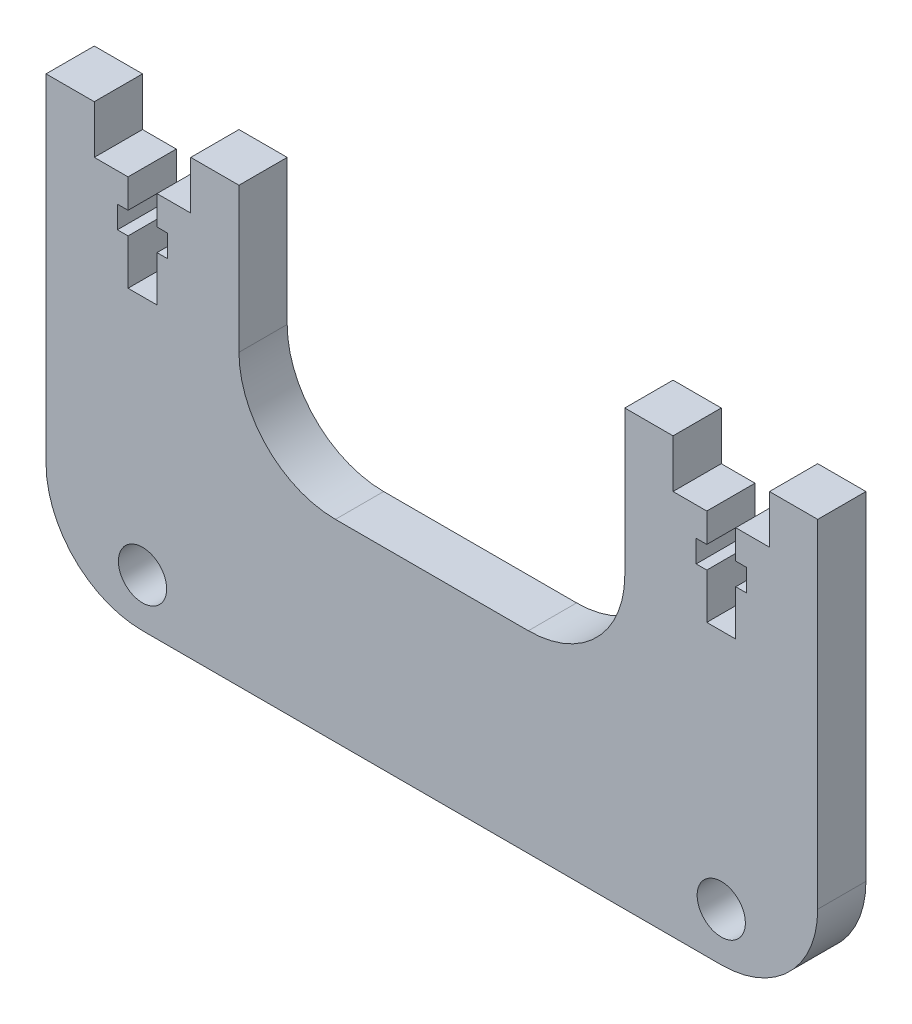
SolidWorks part; units mm, degrees
ref_plane "Plan de face" through (0, 0, 0) normal (0, 0, 1) x (1, 0, 0)
ref_plane "Plan de dessus" through (0, 0, 0) normal (0, 1, 0) x (1, 0, 0)
ref_plane "Plan de droite" through (0, 0, 0) normal (1, 0, 0) x (0, 0, -1)
sketch "Esquisse1" plane through (0, 0, 0) normal (0, 0, 1) x (1, 0, 0)
  line L0 (0, 0) -> (40, 0) construction
  line L1 (0, 0) -> (0, 31.2901) construction
  line L2 (-40, 0) -> (-40, -40)
  line L3 (-40, -40) -> (40, -40)
  line L4 (40, -40) -> (40, 0)
  line L5 (-20, 0) -> (-20, -20)
  line L6 (-20, -20) -> (20, -20)
  line L7 (20, -20) -> (20, 0)
  line L8 (-40, -35) -> (40, -35) construction
  circle A0 centre (-30, -35) radius 2.5
  circle A2 centre (30, -35) radius 2.5
  line B0 (32.6, -3) -> (32.6, -5.3)
  line B1 (28.5, -5.3) -> (28.5, -10)
  line B2 (31.5, -10) -> (31.5, -5.3)
  line B3 (32.6, -5.3) -> (31.5, -5.3)
  line B4 (30, 0) -> (30, -11.2208) construction
  line B5 (31.5, 0) -> (35, 0)
  line B6 (35, 5) -> (40, 5)
  line B7 (40, 5) -> (40, 0)
  line B8 (35, 5) -> (35, 0)
  line B9 (28.5, 0) -> (25, 0)
  line B10 (25, 0) -> (25, 5)
  line B11 (25, 5) -> (20, 5)
  line B12 (20, 5) -> (20, 0)
  line B13 (31.5, 0) -> (28.5, 0) construction
  line B14 (28.5, 0) -> (28.5, -3)
  line B15 (28.5, -5.3) -> (27.4, -5.3)
  line B16 (27.4, -3) -> (28.5, -3)
  line B17 (28.5, -10) -> (31.5, -10)
  line B18 (31.5, -3) -> (32.6, -3)
  line B19 (27.4, -5.3) -> (27.4, -3)
  line B20 (31.5, -3) -> (31.5, 0)
  line B21 (30, -10) -> (30, 0) construction
  line B22 (-32.6, -3) -> (-32.6, -5.3)
  line B23 (-28.5, -5.3) -> (-28.5, -10)
  line B24 (-31.5, -10) -> (-31.5, -5.3)
  line B25 (-32.6, -5.3) -> (-31.5, -5.3)
  line B26 (-30, 0) -> (-30, -11.2208) construction
  line B27 (-31.5, 0) -> (-35, 0)
  line B28 (-35, 5) -> (-40, 5)
  line B29 (-40, 5) -> (-40, 0)
  line B30 (-35, 5) -> (-35, 0)
  line B31 (-28.5, 0) -> (-25, 0)
  line B32 (-25, 0) -> (-25, 5)
  line B33 (-25, 5) -> (-20, 5)
  line B34 (-20, 5) -> (-20, 0)
  line B35 (-31.5, 0) -> (-28.5, 0) construction
  line B36 (-28.5, 0) -> (-28.5, -3)
  line B37 (-28.5, -5.3) -> (-27.4, -5.3)
  line B38 (-27.4, -3) -> (-28.5, -3)
  line B39 (-28.5, -10) -> (-31.5, -10)
  line B40 (-31.5, -3) -> (-32.6, -3)
  line B41 (-27.4, -5.3) -> (-27.4, -3)
  line B42 (-31.5, -3) -> (-31.5, 0)
  line B43 (-30, -10) -> (-30, 0) construction
  dimension "D5" = 5
  dimension "D1" = 60
  dimension "D2" = 20
  dimension "D3" = 20
  dimension "D4" = 5
sketch_block_instance "Insert M3 plots ep 5mm-1"
sketch_block "Insert M3 plots ep 5mm" parameters "D1"=10, "D2"=5, "D3"=5
sketch_block_instance "Decoupe Insert M3-4"
sketch_block "Decoupe Insert M3" parameters "D1"=5.2, "D2"=3, "D3"=2.3, "D4"=3, "D5"=10
sketch_block_instance "Insert M3 plots ep 5mm-3"
extrude "Boss.-Extru.1" add sketch "Esquisse1" along normal blind 5 contours B40 B42 B27 B30 B28 B29 L2 L3 L4 B7 B6 B8 B5 B20 B18 B0 B3 B2 B17 B1 B15 B19 B16 B14 B9 B10 B11 B12 L7 L6 L5 B34 B33 B32 B31 B36 B38 B41 B37 B23 B39 B24 B25 B22 A2 A0
fillet "Congé1" radius 10 4 edges at (-40, -40, 2.5) (40, -40, 2.5) (20, -20, 2.5) (-20, -20, 2.5)
